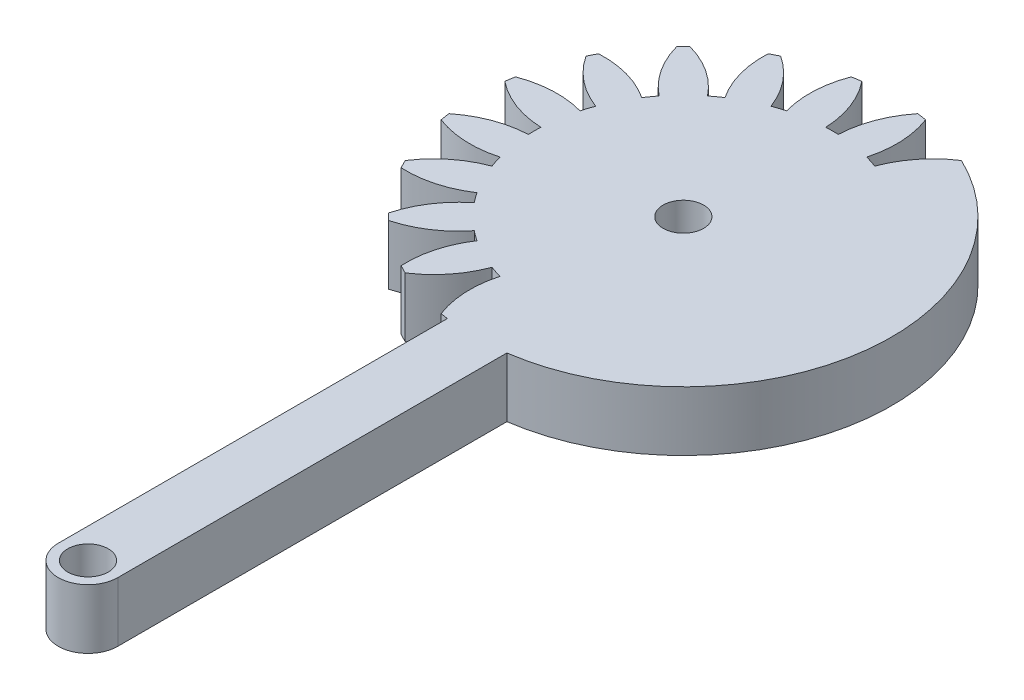
SolidWorks part; units mm, degrees
material "PET"
ref_plane "Front Plane" through (0, 0, 0) normal (0, 0, 1) x (1, 0, 0)
ref_plane "Top Plane" through (0, 0, 0) normal (0, 1, 0) x (1, 0, 0)
ref_plane "Right Plane" through (0, 0, 0) normal (1, 0, 0) x (0, 0, -1)
sketch "Sketch1" plane through (0, 0, 0) normal (0, 1, 0) x (1, 0, 0)
  circle A0 centre (0, 0) radius 2.159
  circle A1 centre (0, 0) radius 19.05 construction
  circle A2 centre (0, 0) radius 22.225
  dimension "D1" = 4.318
  dimension "D2" = 38.1
  dimension "D3" = 3.175
extrude "Boss-Extrude1" add sketch "Sketch1" along normal blind 6.35
sketch "Sketch2" plane through (0, 6.35, 0) normal (0, 1, 0) x (1, 0, 0)
  line L0 (0, 0) -> (0, 22.225) construction
  line L1 (-0.6646, 15.8611) -> (0, 0) construction
  line L2 (-3.0927, 23.9733) -> (0, 15.4763) construction
  circle A0 centre (0, 0) radius 19.05 construction
  circle A1 centre (0, 0) radius 22.225 construction
  arc A2 (0.6646, 15.8611) -> (-0.6646, 15.8611) centre (0, 0) ccw
  arc A3 (2.9833, 22.0239) -> (-2.9833, 22.0239) centre (0, 0) ccw
  arc A4 (-0.6646, 15.8611) -> (-2.9833, 22.0239) centre (-11.1857, 15.4202) ccw
  arc A5 (0.6646, 15.8611) -> (2.9833, 22.0239) centre (11.1857, 15.4202) cw
  circle A6 centre (0, 0) radius 15.875 construction
  dimension "D1" = 38.1
  dimension "D3" = 20
  dimension "D4" = 5.9847
  dimension "D2" = 3.175
extrude "Cut-Extrude1" cut sketch "Sketch2" against normal through all contours A3 A4 A2 A5
pattern_circular "CirPattern1" count 20 over 360 about axis through (0, 0, 0) along (0, 1, 0) of "Cut-Extrude1"
sketch "Sketch3" plane through (0, 6.35, 0) normal (0, 1, 0) x (1, 0, 0)
  line L2 (0, 0) -> (0, -63.5) construction
  line L3 (3.175, -21.997) -> (3.175, -63.5)
  line L4 (-3.175, 4.5875) -> (-3.175, -63.5)
  line L5 (-3.175, 4.5875) -> (10.0899, 19.8026)
  arc A4 (-3.175, -63.5) -> (3.175, -63.5) centre (0, -63.5) ccw
  arc A5 (10.5317, 19.5712) -> (9.6431, 20.024) centre (0, 0) ccw construction
  arc A6 (10.0899, 19.8026) -> (3.175, -21.997) centre (0, 0) cw
  arc A7 (21.8678, -3.9684) -> (22.0239, -2.9833) centre (0, 0) ccw construction
  circle A8 centre (0, -63.5) radius 2.159
  circle A9 centre (0, 0) radius 2.159
  point P1 (-3.175, 4.5875)
  point P3 (0, -19.05)
  dimension "D1" = 6.35
  dimension "D2" = 63.5
  dimension "D3" = 4.318
  dimension "D4" = 4.318
extrude "Boss-Extrude2" add sketch "Sketch3" against normal up to surface (6.35 mm away)
equation "\"P.D\"= 1.5"
equation "\"N\"= 20"
equation "\"D1@Sketch2\"=\"P.D\""
equation "\"D4@Sketch2\"=(\"P.D\"*pi)/\"N\""
